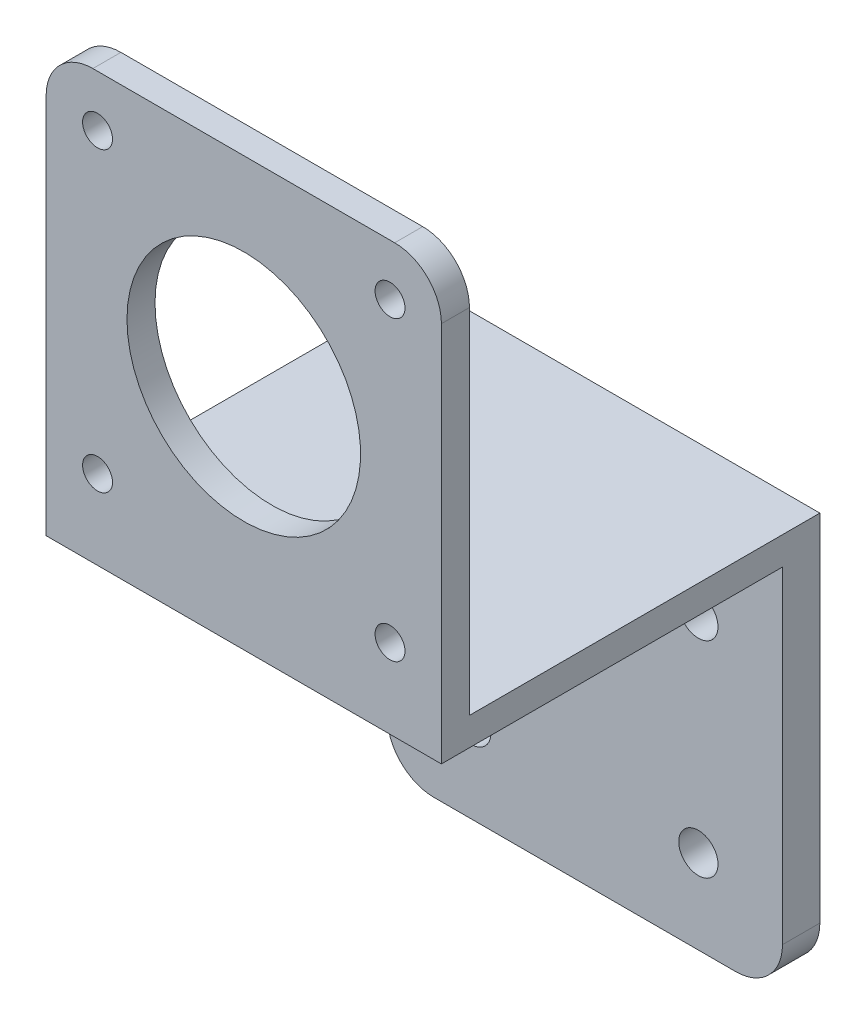
SolidWorks part; units mm, degrees
ref_plane "Front Plane" through (0, 0, 0) normal (0, 0, 1) x (1, 0, 0)
ref_plane "Top Plane" through (0, 0, 0) normal (0, 1, 0) x (1, 0, 0)
ref_plane "Right Plane" through (0, 0, 0) normal (1, 0, 0) x (0, 0, -1)
sketch "Sketch1" plane through (0, 0, 0) normal (0, 0, 1) x (1, 0, 0)
  line L1 (-21.15, 21.4) -> (21.15, 21.4)
  line L2 (-21.15, 21.4) -> (-21.15, -21.4)
  line L3 (-21.15, -21.4) -> (21.15, -21.4)
  line L4 (21.15, 21.4) -> (21.15, -21.4)
  line L5 (-21.15, 21.4) -> (21.15, -21.4) construction
  line L6 (-21.15, -21.4) -> (21.15, 21.4) construction
  point P0 (0, 0)
  dimension "D1" = 42.8
  dimension "D2" = 42.3
extrude "Boss-Extrude1" add sketch "Sketch1" along normal blind 3
sketch "Sketch6" plane through (0, 0, 0) normal (0, 0, -1) x (-1, 0, 0)
  line L0 (-21.15, 21.4) -> (21.15, 21.4) construction
  line L1 (-21.15, -21.4) -> (-21.15, 21.4) construction
  line L2 (21.15, 21.4) -> (21.15, -21.4) construction
  line L3 (21.15, -21.4) -> (-21.15, -21.4) construction
  circle A0 centre (0, 0) radius 12.5
  circle A1 centre (-15.65, 15.9) radius 1.6
  circle A2 centre (15.65, 15.9) radius 1.6
  circle A3 centre (-15.65, -15.9) radius 1.6
  circle A4 centre (15.65, -15.9) radius 1.6
  dimension "D1" = 25
  dimension "D2" = 3.2
  dimension "D3" = 3.2
  dimension "D4" = 3.2
  dimension "D5" = 3.2
  dimension "D6" = 5.5
  dimension "D7" = 5.5
  dimension "D8" = 5.5
  dimension "D9" = 5.5
  dimension "D10" = 5.5
  dimension "D11" = 5.5
  dimension "D12" = 5.5
  dimension "D13" = 5.5
extrude "Cut-Extrude3" cut sketch "Sketch6" against normal through all
sketch "Sketch7" plane through (0, -21.4, 0) normal (0, -1, 0) x (1, 0, 0)
  line L0 (21.15, 3) -> (21.15, 0) construction
  line L1 (-21.15, 3) -> (21.15, 3)
  line L2 (-21.15, 3) -> (-21.15, -37.5)
  line L3 (-21.15, -37.5) -> (21.15, -37.5)
  line L4 (21.15, 3) -> (21.15, -37.5)
  dimension "D1" = 40.5
extrude "Boss-Extrude2" add sketch "Sketch7" along normal blind 3
sketch "Sketch8" plane through (0, -24.4, 0) normal (0, -1, 0) x (1, 0, 0)
  line L0 (21.15, -37.5) -> (21.15, 3) construction
  line L1 (-21.15, -37.5) -> (21.15, -37.5)
  line L2 (-21.15, -37.5) -> (-21.15, -33.5)
  line L3 (-21.15, -33.5) -> (21.15, -33.5)
  line L4 (21.15, -37.5) -> (21.15, -33.5)
  dimension "D1" = 4
extrude "Boss-Extrude3" add sketch "Sketch8" along normal blind 40
sketch "Sketch10" plane through (0, 0, -33.5) normal (0, 0, 1) x (1, 0, 0)
  line L0 (-21.15, -64.4) -> (-21.15, -24.4) construction
  line L1 (21.15, -24.4) -> (-21.15, -24.4) construction
  line L2 (21.15, -64.4) -> (21.15, -24.4) construction
  line L3 (21.15, -64.4) -> (-21.15, -64.4) construction
  circle A0 centre (-12.15, -33.4) radius 2.1
  circle A1 centre (12.15, -33.4) radius 2.1
  circle A2 centre (-12.15, -55.4) radius 2.1
  circle A3 centre (12.15, -55.4) radius 2.1
  dimension "D3" = 4.2
  dimension "D1" = 9
  dimension "D2" = 9
  dimension "D4" = 9
  dimension "D5" = 9
extrude "Cut-Extrude4" cut sketch "Sketch10" against normal through all
fillet "Fillet1" radius 5 4 edges at (-21.15, 21.4, 1.5) (21.15, 21.4, 1.5) (21.15, -64.4, -35.5) (-21.15, -64.4, -35.5)
